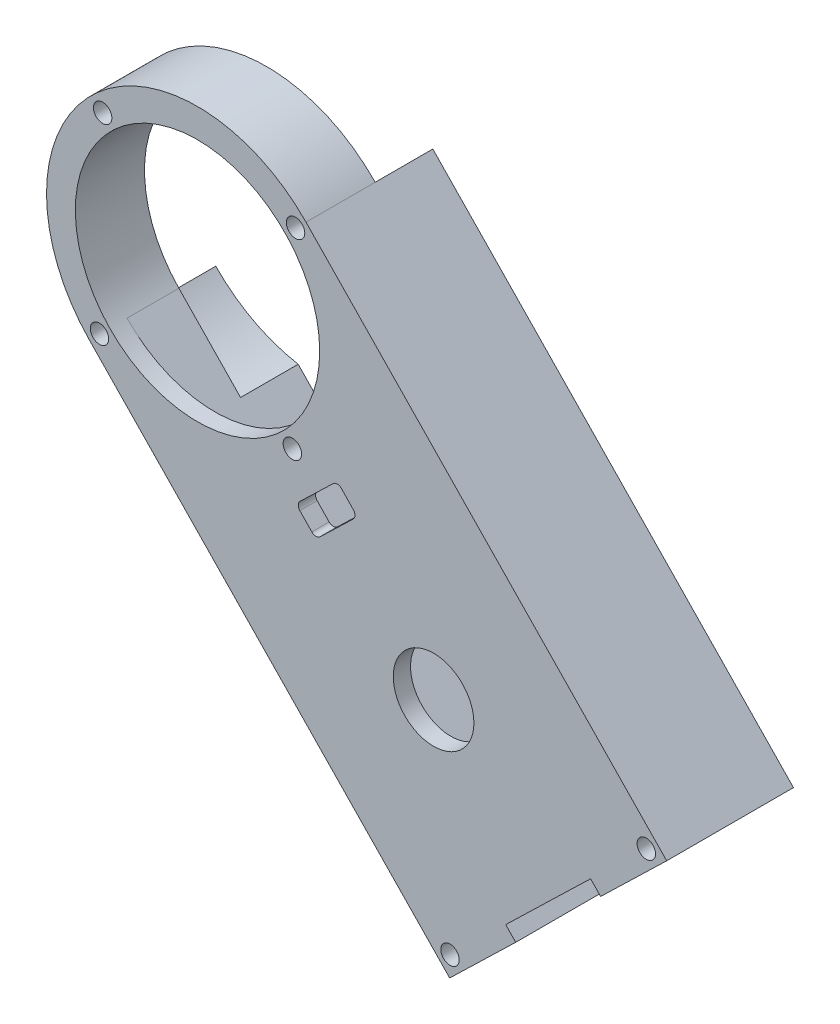
SolidWorks part; units mm, degrees
ref_plane "Front Plane" through (0, 0, 0) normal (0, 0, 1) x (1, 0, 0)
ref_plane "Top Plane" through (0, 0, 0) normal (0, 1, 0) x (1, 0, 0)
ref_plane "Right Plane" through (0, 0, 0) normal (1, 0, 0) x (0, 0, -1)
sketch "Sketch2" plane through (0, 0, 0) normal (0, 0, 1) x (1, 0, 0)
  line L0 (37.4687, -8.236) -> (74.3417, -46.3438) construction
  line L1 (43.8707, -75.8274) -> (6.9978, -37.7196) construction
  line L2 (74.3417, -46.3438) -> (43.8707, -75.8274) construction
  line L3 (37.4687, -8.236) -> (74.3417, -46.3438)
  line L4 (43.8707, -75.8274) -> (6.9978, -37.7196)
  line L5 (74.3417, -46.3438) -> (43.8707, -75.8274)
  line L6 (-15.2355, -14.7418) -> (6.9978, -37.7196)
  line L7 (81.4118, -46.4603) -> (18.8287, 18.2186)
  line L8 (-18.8287, -18.2186) -> (43.7543, -82.8975)
  line L9 (43.7543, -82.8975) -> (55.2169, -71.8064)
  line L10 (55.2169, -71.8064) -> (53.4784, -70.0098)
  line L11 (53.4784, -70.0098) -> (68.2109, -55.7548)
  line L12 (68.2109, -55.7548) -> (69.9493, -57.5514)
  line L13 (69.9493, -57.5514) -> (81.4118, -46.4603)
  line L14 (81.4118, -46.4603) -> (18.8287, 18.2186)
  line L15 (-18.8287, -18.2186) -> (43.7543, -82.8975)
  line L16 (43.7543, -82.8975) -> (55.2169, -71.8064)
  line L17 (55.2169, -71.8064) -> (53.4784, -70.0098)
  line L18 (53.4784, -70.0098) -> (68.2109, -55.7548)
  line L19 (68.2109, -55.7548) -> (69.9493, -57.5514)
  line L20 (69.9493, -57.5514) -> (81.4118, -46.4603)
  line L21 (15.2355, 14.7418) -> (37.4687, -8.236)
  arc A0 (15.2355, 14.7418) -> (-15.2355, -14.7418) centre (0, 0) ccw
  arc A1 (18.8287, 18.2186) -> (-18.8287, -18.2186) centre (0, 0) ccw
  arc A2 (18.8287, 18.2186) -> (-18.8287, -18.2186) centre (0, 0) ccw
  dimension "D1" = 0
  dimension "D2" = 5
extrude "Boss-Extrude1" add sketch "Sketch2" along normal blind 22
sketch "Sketch3" plane through (0, 0, 0) normal (0, 0, -1) x (-1, 0, 0)
  circle A0 centre (0, 0) radius 26.2
extrude "Cut-Extrude1" cut sketch "Sketch3" against normal blind 10
sketch "Sketch4" plane through (0, 0, 22) normal (0, 0, 1) x (1, 0, 0)
  line L0 (43.8707, -75.8274) -> (74.3417, -46.3438) construction
  line L1 (74.3417, -46.3438) -> (15.2355, 14.7418) construction
  line L2 (-15.2355, -14.7418) -> (43.8707, -75.8274) construction
  line L3 (43.8707, -75.8274) -> (74.3417, -46.3438)
  line L4 (74.3417, -46.3438) -> (15.2355, 14.7418)
  line L5 (-15.2355, -14.7418) -> (43.8707, -75.8274)
  line L8 (24.9654, -18.7264) -> (27.0459, -20.8878)
  line L9 (23.5515, -18.6994) -> (17.7878, -24.2474)
  line L10 (27.0189, -22.3017) -> (21.2552, -27.8497)
  line L11 (17.7608, -25.6613) -> (19.8413, -27.8227)
  arc A0 (-15.2355, -14.7418) -> (15.2355, 14.7418) centre (0, 0) ccw
  circle A1 centre (40.9617, -42.4773) radius 7
  arc A3 (17.7878, -24.2474) -> (17.7608, -25.6613) centre (18.4813, -24.9679) ccw
  arc A4 (19.8413, -27.8227) -> (21.2552, -27.8497) centre (20.5617, -27.1292) ccw
  arc A5 (27.0189, -22.3017) -> (27.0459, -20.8878) centre (26.3254, -21.5813) ccw
  arc A6 (24.9654, -18.7264) -> (23.5515, -18.6994) centre (24.245, -19.4199) ccw
  point P16 (22.4034, -23.2746)
  dimension "D1" = 1
extrude "Boss-Extrude2" add sketch "Sketch4" against normal blind 3
sketch "Sketch5" plane through (62.5831, -64.6789, 0) normal (0.6954, -0.7187, 0) x (0.7187, 0.6954, 0)
  circle A0 centre (15.5, 11.5) radius 1.8
  circle A1 centre (-15.5, 11.5) radius 1.8
extrude "Cut-Extrude2" cut sketch "Sketch5" against normal blind 5
sketch "Sketch6" plane through (0, 0, 22) normal (0, 0, 1) x (1, 0, 0)
  circle A0 centre (77.8768, -46.4021) radius 1.6
  circle A1 centre (43.8125, -79.3625) radius 1.6
extrude "Cut-Extrude3" cut sketch "Sketch6" against normal through all
sketch "Sketch7" plane through (0, 0, 22) normal (0, 0, 1) x (1, 0, 0)
  circle A0 centre (-16.4611, 17.0124) radius 1.6 construction
  circle A1 centre (-16.4611, 17.0124) radius 1.6
  circle A2 centre (17.0124, 16.4611) radius 1.6
  circle A3 centre (16.4611, -17.0124) radius 1.6
  circle A4 centre (-17.0124, -16.4611) radius 1.6
  point P12 (0, 0)
  dimension "D1" = 4
extrude "Cut-Extrude4" cut sketch "Sketch7" against normal through all
